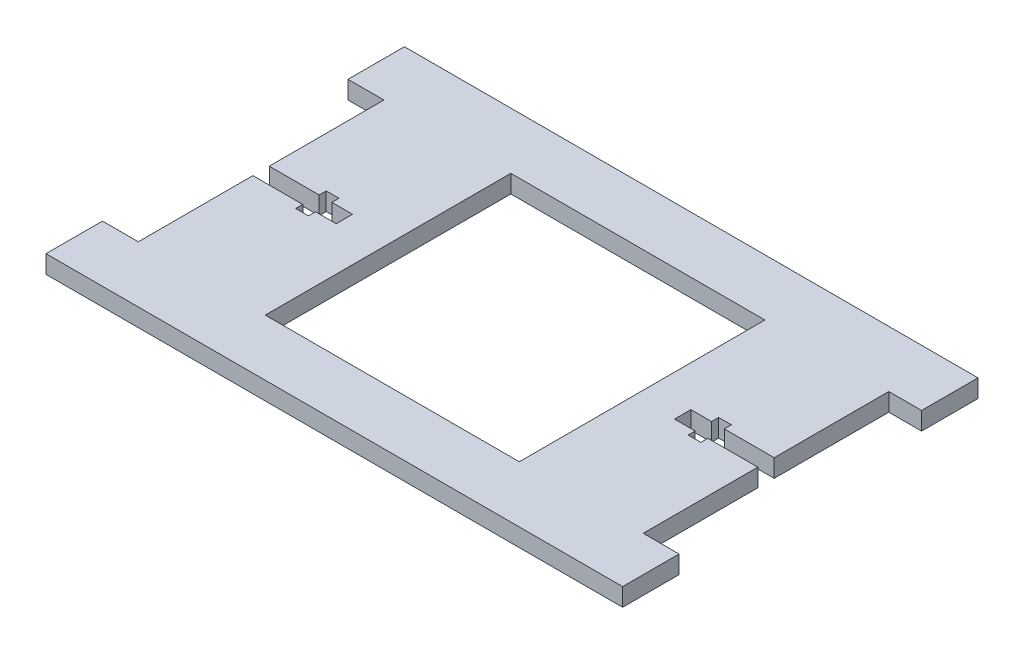
SolidWorks part; units mm, degrees
ref_plane "Front Plane" through (0, 0, 0) normal (0, 0, 1) x (1, 0, 0)
ref_plane "Top Plane" through (0, 0, 0) normal (0, 1, 0) x (1, 0, 0)
ref_plane "Right Plane" through (0, 0, 0) normal (1, 0, 0) x (0, 0, -1)
sketch "Sketch1" plane through (0, 0, 0) normal (0, 1, 0) x (1, 0, 0)
  line L0 (37.2275, -45.3753) -> (37.2275, -35.3753)
  line L1 (-64.9171, 18.1247) -> (36.6829, 18.1247)
  line L2 (30.8775, -35.3753) -> (30.8775, -15.0753)
  line L3 (-64.9171, -45.3753) -> (37.2275, -45.3753)
  line L4 (36.6829, 18.1247) -> (36.6829, 8.1247)
  line L5 (36.6829, 8.1247) -> (30.8775, 8.1247)
  line L6 (22.0375, -12.1753) -> (30.8775, -12.1753)
  line L7 (37.2275, -35.3753) -> (30.8775, -35.3753)
  line L8 (16.1275, -12.1753) -> (19.7875, -12.1753)
  line L9 (16.1275, -12.1753) -> (16.1275, -15.0753)
  line L10 (16.1275, -15.0753) -> (19.7875, -15.0753)
  line L11 (-64.9171, 8.1247) -> (-58.5671, 8.1247)
  line L12 (19.7875, -16.3253) -> (22.0375, -16.3253)
  line L13 (19.7875, -16.3253) -> (19.7875, -15.0753)
  line L14 (19.7875, -10.9253) -> (22.0375, -10.9253)
  line L15 (22.0375, -16.3253) -> (22.0375, -15.0753)
  line L16 (22.0375, -15.0753) -> (30.8775, -15.0753)
  line L17 (19.7875, -12.1753) -> (19.7875, -10.9253)
  line L18 (22.0375, -12.1753) -> (22.0375, -10.9253)
  line L19 (30.8775, -12.1753) -> (30.8775, 8.1247)
  line L21 (-49.7271, -12.1753) -> (-58.5671, -12.1753)
  line L22 (-49.7271, -12.1753) -> (-49.7271, -10.9253)
  line L23 (-47.4771, -12.1753) -> (-47.4771, -10.9253)
  line L24 (-49.7271, -15.0753) -> (-58.5671, -15.0753)
  line L25 (-49.7271, -16.3253) -> (-49.7271, -15.0753)
  line L26 (-47.4771, -10.9253) -> (-49.7271, -10.9253)
  line L27 (-47.4771, -16.3253) -> (-47.4771, -15.0753)
  line L28 (-47.4771, -16.3253) -> (-49.7271, -16.3253)
  line L29 (-43.8171, -15.0753) -> (-47.4771, -15.0753)
  line L30 (-43.8171, -12.1753) -> (-43.8171, -15.0753)
  line L31 (-43.8171, -12.1753) -> (-47.4771, -12.1753)
  line L32 (-64.9171, -35.3753) -> (-58.5671, -35.3753)
  line L33 (-58.5671, -35.3753) -> (-58.5671, -15.0753)
  line L34 (-64.9171, -45.3753) -> (-64.9171, -35.3753)
  line L35 (-58.5671, -12.1753) -> (-58.5671, 8.1247)
  line L36 (-64.9171, 18.1247) -> (-64.9171, 8.1247)
  line L37 (-36.0725, 8.1247) -> (8.9275, 8.1247)
  line L38 (-36.0725, 8.1247) -> (-36.0725, -35.3753)
  line L39 (-36.0725, -35.3753) -> (8.9275, -35.3753)
  line L40 (8.9275, 8.1247) -> (8.9275, -35.3753)
  point P40 (-13.5725, -35.3753)
  dimension "D1" = 101.6
  dimension "D2" = 63.5
  dimension "D3" = 10
  dimension "D4" = 10
  dimension "D5" = 6.35
  dimension "D6" = 20.3
  dimension "D7" = 20.3
  dimension "D8" = 2.9
  dimension "D9" = 14.75
  dimension "D10" = 2.25
  dimension "D11" = 1.25
  dimension "D12" = 8.84
  dimension "D13" = 1.25
  dimension "D14" = 43.5
  dimension "D15" = 45
  dimension "D16" = 10
  dimension "D17" = 50.8
extrude "Extrude1" add sketch "Sketch1" along normal blind 3.175
